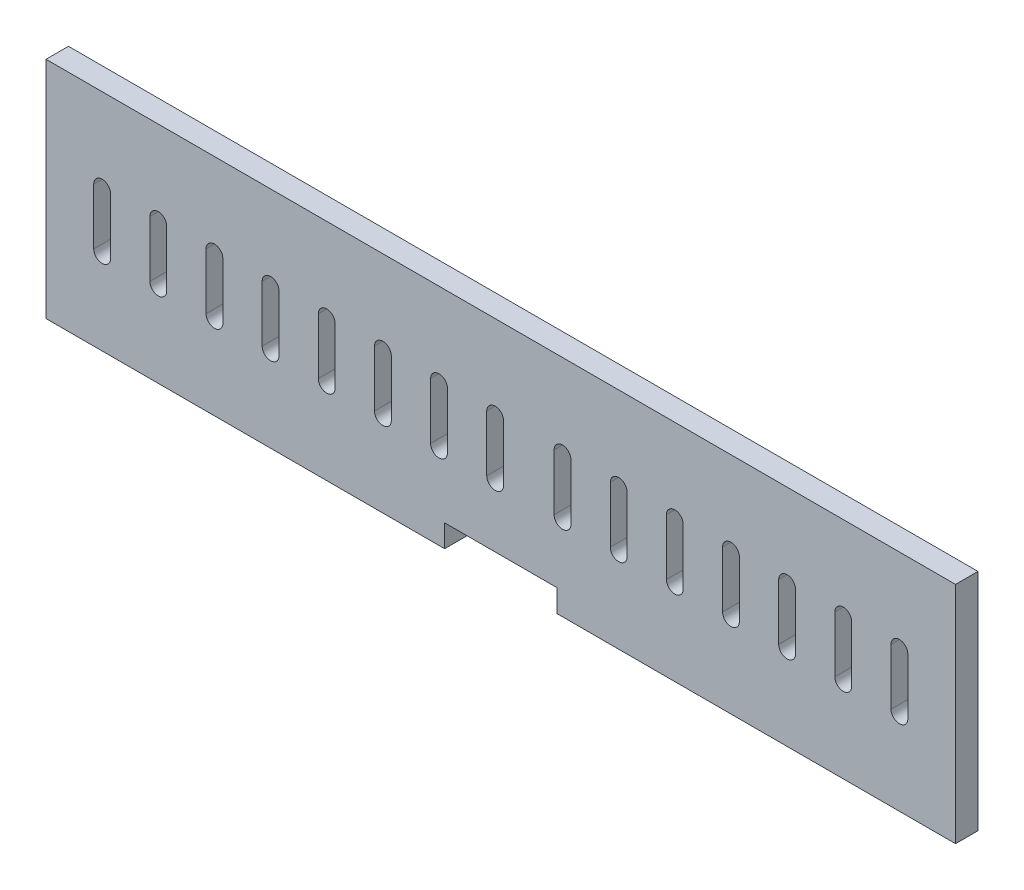
SolidWorks part; units mm, degrees
ref_plane "Front Plane" through (0, 0, 0) normal (0, 0, 1) x (1, 0, 0)
ref_plane "Top Plane" through (0, 0, 0) normal (0, 1, 0) x (1, 0, 0)
ref_plane "Right Plane" through (0, 0, 0) normal (1, 0, 0) x (0, 0, -1)
sketch "Sketch1" plane through (0, 0, 0) normal (0, 0, 1) x (1, 0, 0)
  line L0 (10, -15) -> (10, -25) construction
  line L1 (0, 0) -> (162, 0)
  line L2 (0, 0) -> (0, -40)
  line L3 (0, -40) -> (162, -40)
  line L4 (162, 0) -> (162, -40)
  line L5 (71, -36) -> (91, -36)
  line L6 (71, -36) -> (71, -40)
  line L7 (71, -40) -> (91, -40)
  line L8 (91, -36) -> (91, -40)
  line L9 (11.5, -15) -> (11.5, -25)
  line L10 (8.5, -15) -> (8.5, -25)
  line L11 (15, 0) -> (15, -40) construction
  line L12 (20, -15) -> (20, -25) construction
  line L13 (18.5, -15) -> (18.5, -25)
  line L14 (21.5, -15) -> (21.5, -25)
  line L15 (25, 0) -> (25, -41.8411) construction
  line L16 (30, -15) -> (30, -25) construction
  line L17 (31.5, -15) -> (31.5, -25)
  line L18 (28.5, -15) -> (28.5, -25)
  line L19 (40, -15) -> (40, -25) construction
  line L20 (38.5, -15) -> (38.5, -25)
  line L21 (41.5, -15) -> (41.5, -25)
  line L22 (45, 0) -> (45, -41.8411) construction
  line L23 (50, -15) -> (50, -25) construction
  line L24 (51.5, -15) -> (51.5, -25)
  line L25 (48.5, -15) -> (48.5, -25)
  line L26 (60, -15) -> (60, -25) construction
  line L27 (58.5, -15) -> (58.5, -25)
  line L28 (61.5, -15) -> (61.5, -25)
  line L29 (70, -15) -> (70, -25) construction
  line L30 (71.5, -15) -> (71.5, -25)
  line L31 (68.5, -15) -> (68.5, -25)
  line L32 (80, -15) -> (80, -25) construction
  line L33 (78.5, -15) -> (78.5, -25)
  line L34 (81.5, -15) -> (81.5, -25)
  line L35 (81, 0) -> (81, -41.8411) construction
  line L36 (142, -15) -> (142, -25) construction
  line L37 (143.5, -15) -> (143.5, -25)
  line L38 (140.5, -15) -> (140.5, -25)
  line L39 (152, -15) -> (152, -25) construction
  line L40 (150.5, -15) -> (150.5, -25)
  line L41 (153.5, -15) -> (153.5, -25)
  line L42 (132, -15) -> (132, -25) construction
  line L43 (130.5, -15) -> (130.5, -25)
  line L44 (133.5, -15) -> (133.5, -25)
  line L45 (122, -15) -> (122, -25) construction
  line L46 (123.5, -15) -> (123.5, -25)
  line L47 (120.5, -15) -> (120.5, -25)
  line L48 (112, -15) -> (112, -25) construction
  line L49 (110.5, -15) -> (110.5, -25)
  line L50 (113.5, -15) -> (113.5, -25)
  line L51 (102, -15) -> (102, -25) construction
  line L52 (103.5, -15) -> (103.5, -25)
  line L53 (100.5, -15) -> (100.5, -25)
  line L54 (92, -15) -> (92, -25) construction
  line L55 (90.5, -15) -> (90.5, -25)
  line L56 (93.5, -15) -> (93.5, -25)
  arc A0 (11.5, -15) -> (8.5, -15) centre (10, -15) ccw
  arc A1 (8.5, -25) -> (11.5, -25) centre (10, -25) ccw
  arc A2 (18.5, -15) -> (21.5, -15) centre (20, -15) cw
  arc A3 (21.5, -25) -> (18.5, -25) centre (20, -25) cw
  arc A4 (31.5, -15) -> (28.5, -15) centre (30, -15) ccw
  arc A5 (28.5, -25) -> (31.5, -25) centre (30, -25) ccw
  arc A6 (38.5, -15) -> (41.5, -15) centre (40, -15) cw
  arc A7 (41.5, -25) -> (38.5, -25) centre (40, -25) cw
  arc A8 (51.5, -15) -> (48.5, -15) centre (50, -15) ccw
  arc A9 (48.5, -25) -> (51.5, -25) centre (50, -25) ccw
  arc A10 (58.5, -15) -> (61.5, -15) centre (60, -15) cw
  arc A11 (61.5, -25) -> (58.5, -25) centre (60, -25) cw
  arc A12 (71.5, -15) -> (68.5, -15) centre (70, -15) ccw
  arc A13 (68.5, -25) -> (71.5, -25) centre (70, -25) ccw
  arc A14 (78.5, -15) -> (81.5, -15) centre (80, -15) cw
  arc A15 (81.5, -25) -> (78.5, -25) centre (80, -25) cw
  arc A16 (143.5, -15) -> (140.5, -15) centre (142, -15) ccw
  arc A17 (140.5, -25) -> (143.5, -25) centre (142, -25) ccw
  arc A18 (150.5, -15) -> (153.5, -15) centre (152, -15) cw
  arc A19 (153.5, -25) -> (150.5, -25) centre (152, -25) cw
  arc A20 (130.5, -15) -> (133.5, -15) centre (132, -15) cw
  arc A21 (133.5, -25) -> (130.5, -25) centre (132, -25) cw
  arc A22 (123.5, -15) -> (120.5, -15) centre (122, -15) ccw
  arc A23 (120.5, -25) -> (123.5, -25) centre (122, -25) ccw
  arc A24 (110.5, -15) -> (113.5, -15) centre (112, -15) cw
  arc A25 (113.5, -25) -> (110.5, -25) centre (112, -25) cw
  arc A26 (103.5, -15) -> (100.5, -15) centre (102, -15) ccw
  arc A27 (100.5, -25) -> (103.5, -25) centre (102, -25) ccw
  arc A28 (90.5, -15) -> (93.5, -15) centre (92, -15) cw
  arc A29 (93.5, -25) -> (90.5, -25) centre (92, -25) cw
  point P9 (81, -36)
  point P12 (10, -20)
  point P21 (20, -20)
  point P30 (30, -20)
  point P37 (40, -20)
  point P46 (50, -20)
  point P53 (60, -20)
  point P60 (70, -20)
  point P67 (80, -20)
  point P76 (142, -20)
  point P83 (152, -20)
  point P90 (132, -20)
  point P97 (122, -20)
  point P104 (112, -20)
  point P111 (102, -20)
  point P118 (92, -20)
  dimension "D7" = 1.5
  dimension "D1" = 162
  dimension "D2" = 40
  dimension "D3" = 4
  dimension "D4" = 20
  dimension "D5" = 81
  dimension "D6" = 10
  dimension "D8" = 10
  dimension "D9" = 20
  dimension "D10" = 15
  dimension "D11" = 25
  dimension "D12" = 45
extrude "Boss-Extrude1" add sketch "Sketch1" along normal blind 4 contours L5 L8 L3 L4 L1 L2 L6
